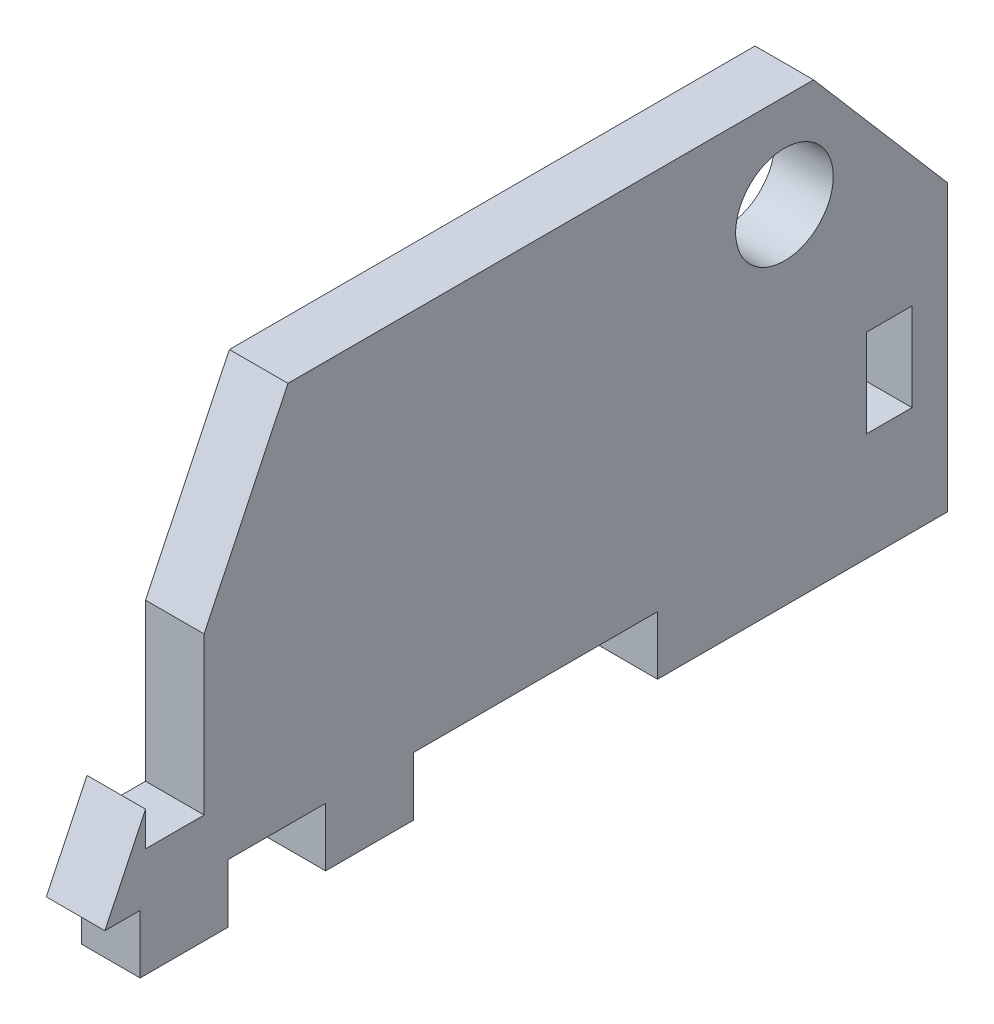
SolidWorks part; units mm, degrees
ref_plane "Front Plane" through (0, 0, 0) normal (0, 0, 1) x (1, 0, 0)
ref_plane "Top Plane" through (0, 0, 0) normal (0, 1, 0) x (1, 0, 0)
ref_plane "Right Plane" through (0, 0, 0) normal (1, 0, 0) x (0, 0, -1)
sketch "Sketch1" plane through (0, 0, 0) normal (1, 0, 0) x (0, 0, -1)
  line L0 (-53.777, -34.8814) -> (-50.1671, -34.8814)
  line L1 (-50.1671, -34.8814) -> (-50.1671, -40.8814)
  line L2 (-50.1671, -40.8814) -> (-41.1671, -40.8814)
  line L3 (-41.1671, -40.8814) -> (-41.1671, -34.8814)
  line L4 (-41.1671, -34.8814) -> (-31.1671, -34.8814)
  line L5 (-31.1671, -34.8814) -> (-31.1671, -40.8814)
  line L6 (-31.1671, -40.8814) -> (-22.1671, -40.8814)
  line L7 (-22.1671, -40.8814) -> (-22.1671, -34.8814)
  line L8 (-22.1671, -34.8814) -> (2.8329, -34.8814)
  line L9 (32.5529, -11.701) -> (32.5529, -40.8814)
  line L10 (32.5529, -40.8814) -> (2.8329, -40.8814)
  line L11 (15.8329, -5.2639) -> (2.8329, -5.2639) construction
  line L13 (2.8329, -34.8814) -> (2.8329, -40.8814)
  line L18 (32.5529, -11.701) -> (18.8209, 4.304)
  line L19 (18.8209, 4.304) -> (-35.0291, 4.304)
  line L20 (-35.0291, 4.304) -> (-53.777, -34.8814)
  line L22 (24.2168, -29.8154) -> (28.8987, -29.8154)
  line L23 (24.2168, -29.8154) -> (24.2168, -20.7941)
  line L24 (24.2168, -20.7941) -> (28.8987, -20.7941)
  line L25 (28.8987, -29.8154) -> (28.8987, -20.7941)
  line L26 (-49.6138, -11.8533) -> (-43.6138, -11.8533)
  line L27 (-49.6138, -11.8533) -> (-49.6138, -29.7012)
  line L28 (-49.6138, -29.7012) -> (-43.6138, -29.7012)
  line L29 (-43.6138, -11.8533) -> (-43.6138, -29.7012)
  circle A0 centre (15.8329, -5.2639) radius 5
extrude "Boss-Extrude1" add sketch "Sketch1" along normal blind 6
